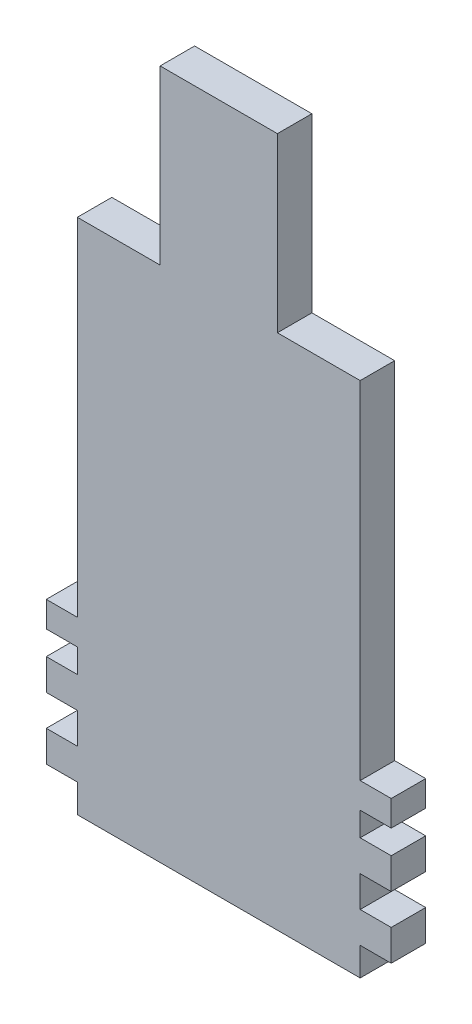
SolidWorks part; units mm, degrees
ref_plane "Plan de face" through (0, 0, 0) normal (0, 0, 1) x (1, 0, 0)
ref_plane "Plan de dessus" through (0, 0, 0) normal (0, 1, 0) x (1, 0, 0)
ref_plane "Plan de droite" through (0, 0, 0) normal (1, 0, 0) x (0, 0, -1)
sketch "Esquisse1" plane through (0, 0, 0) normal (0, 0, 1) x (1, 0, 0)
  line L5 (-47.9214, 34.7802) -> (-47.9214, 38.8802)
  line L6 (-43.4214, 38.8802) -> (-47.9214, 38.8802)
  line L7 (-43.4214, 38.8802) -> (-43.4214, 43.3802)
  line L8 (-43.4214, 43.3802) -> (-47.9214, 43.3802)
  line L9 (-47.9214, 43.3802) -> (-47.9214, 47.8802)
  line L10 (-43.4214, 47.8802) -> (-47.9214, 47.8802)
  line L11 (-43.4214, 47.8802) -> (-43.4214, 52.3802)
  line L12 (-43.4214, 52.3802) -> (-47.9214, 52.3802)
  line L13 (-47.9214, 52.3802) -> (-47.9214, 55.8443)
  line L14 (-43.4214, 55.8443) -> (-47.9214, 55.8443)
  line L15 (-43.4214, 55.8443) -> (-43.4214, 59.5651)
  line L16 (-43.4214, 59.5651) -> (-47.9214, 59.5651)
  line L17 (-47.9214, 59.5651) -> (-47.9214, 109.7802)
  line L21 (-47.9214, 109.7802) -> (-59.9214, 109.7802)
  line L22 (-59.9214, 109.7802) -> (-59.9214, 134.7802)
  line L24 (-47.9214, 34.7802) -> (-88.9214, 34.7802)
  line L26 (-68.4214, 34.7802) -> (-68.4214, 134.7802)
  line L27 (-76.9214, 134.7802) -> (-59.9214, 134.7802)
  line L29 (-88.9214, 34.7802) -> (-88.9214, 38.8802)
  line L30 (-93.4214, 38.8802) -> (-88.9214, 38.8802)
  line L31 (-93.4214, 38.8802) -> (-93.4214, 43.3802)
  line L32 (-93.4214, 43.3802) -> (-88.9214, 43.3802)
  line L33 (-88.9214, 43.3802) -> (-88.9214, 47.8802)
  line L34 (-93.4214, 47.8802) -> (-88.9214, 47.8802)
  line L35 (-93.4214, 47.8802) -> (-93.4214, 52.3802)
  line L36 (-93.4214, 52.3802) -> (-88.9214, 52.3802)
  line L37 (-88.9214, 52.3802) -> (-88.9214, 55.8443)
  line L38 (-93.4214, 55.8443) -> (-88.9214, 55.8443)
  line L39 (-93.4214, 55.8443) -> (-93.4214, 59.5651)
  line L40 (-93.4214, 59.5651) -> (-88.9214, 59.5651)
  line L41 (-88.9214, 59.5651) -> (-88.9214, 109.7802)
  line L42 (-88.9214, 109.7802) -> (-76.9214, 109.7802)
  line L43 (-76.9214, 109.7802) -> (-76.9214, 134.7802)
  point P0 (-45.6714, 59.5651)
  point P19 (-45.6714, 55.8443)
  point P22 (-66.6917, 117.1554)
  dimension "D4" = 4.1
  dimension "D5" = 20.5
  dimension "D6" = 75
  dimension "D7" = 3.7208
  dimension "D8" = 4.5
  dimension "D9" = 4.5
  dimension "D10" = 4.5
  dimension "D11" = 4.5
  dimension "D12" = 4.5
  dimension "D13" = 4.5
  dimension "D14" = 3.4641
  dimension "D15" = 4.5
  dimension "D16" = 4.5
  dimension "D17" = 4.1
  dimension "D18" = 25
  dimension "D19" = 8.5
  dimension "D21" = 3.4641
  dimension "D22" = 4.5
  dimension "D25" = 3.7208
  dimension "D28" = 4.5
  dimension "D30" = 4.5
extrude "Boss.-Extru.1" add sketch "Esquisse1" along normal blind 5
